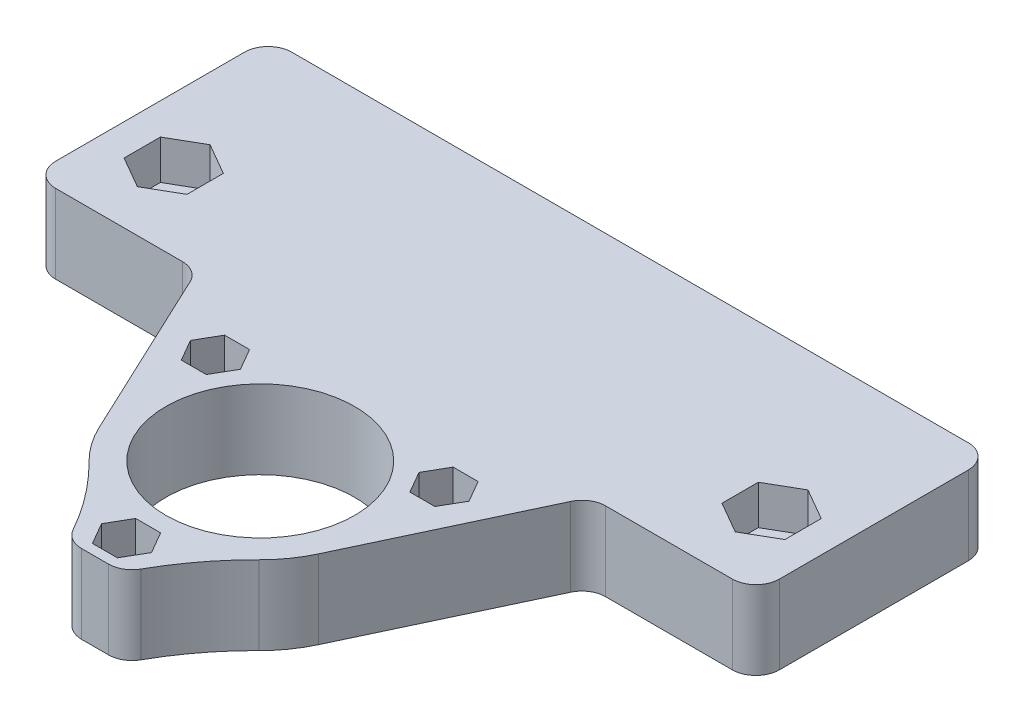
SolidWorks part; units mm, degrees
material "ABS"
ref_plane "Front" through (0, 0, 0) normal (0, 0, 1) x (1, 0, 0)
ref_plane "Top" through (0, 0, 0) normal (0, 1, 0) x (1, 0, 0)
ref_plane "Right" through (0, 0, 0) normal (1, 0, 0) x (0, 0, -1)
sketch "Esquisse1" plane through (0, 0, 0) normal (0, 1, 0) x (1, 0, 0)
  line L0 (0, -50) -> (0, 50) construction
  circle A0 centre (0, -77) radius 12
  circle A1 centre (-38, -50) radius 2.5
  circle A3 centre (-37.5, -115) radius 38
  circle A4 centre (37.5, -115) radius 38
  circle A5 centre (38, -50) radius 2.5
  dimension "D1" = 115
  dimension "D2" = 75
  dimension "D3" = 76
  dimension "D4" = 76
  dimension "D5" = 50
  dimension "D6" = 5
  dimension "D7" = 24
  dimension "D8" = 77
sketch "Esquisse2" plane through (0, 0, 0) normal (0, 1, 0) x (1, 0, 0)
  line L0 (0, -98) -> (-3.5147, -98)
  line L1 (-46, -30) -> (0, -30)
  line L2 (-46, -30) -> (-46, -60)
  line L4 (0, -30) -> (0, -43.5)
  line L5 (0, -89) -> (0, -98)
  line L6 (-46, -60) -> (-25, -60)
  line L7 (-25, -60) -> (-13.9246, -83.5489)
  line L8 (0, -46.5) -> (0, -65)
  line L9 (0, -43.5) -> (0, -46.5)
  circle A0 centre (-38, -50) radius 2.5 construction
  circle A1 centre (0, -77) radius 12 construction
  circle A2 centre (-37.5, -115) radius 38 construction
  circle A3 centre (-38, -50) radius 2.5
  arc A4 (0, -65) -> (0, -89) centre (0, -77) ccw
  arc A5 (-3.5147, -98) -> (-10.8085, -87.9526) centre (-37.5, -115) ccw
  arc A6 (-13.9246, -83.5489) -> (-10.8085, -87.9526) centre (0, -77) ccw
  arc A8 (0, -43.5) -> (0, -46.5) centre (0, -45) ccw construction
  dimension "D1" = 20
  dimension "D4" = 15.3877
  dimension "D5" = 10
  dimension "D7" = 3
  dimension "D8" = 45
  dimension "D2" = 8
  dimension "D3" = 98
  dimension "D6" = 25
extrude "Boss.-Extru.1" add sketch "Esquisse2" along normal blind 10
fillet "Congé1" radius 3 4 edges at (-46, 5, 30) (-46, 5, 60) (-25, 5, 60) (-3.5147, 5, 98)
sketch "Esquisse3" plane through (0, 0, 30) normal (0, 0, -1) x (-1, 0, 0)
  line L0 (0, 21) -> (20, 21) construction
  line L1 (0, 41) -> (20, 41)
  line L2 (0, 1) -> (20, 1)
  line L3 (0, 10) -> (0, 0) construction
  line L4 (0, 0) -> (43, 0) construction
  arc A0 (0, 41) -> (0, 1) centre (0, 21) ccw
  arc A1 (20, 1) -> (20, 41) centre (20, 21) ccw
  point P2 (10, 21)
  dimension "D1" = 21
  dimension "D2" = 40
  dimension "D3" = 20
extrude "Enlèv. mat.-Extru.1" [suppressed] cut sketch "Esquisse3" against normal blind 10
mirror "Symétrie1"
sketch "Esquisse4" plane through (0, 10, 0) normal (0, 1, 0) x (1, 0, 0)
  line L0 (-24.1895, -61.7232) -> (-13.9246, -83.5489) construction
  line L1 (0, -50) -> (0, 50) construction
  circle A0 centre (-14.527, -68.1701) radius 1.25
  circle A1 centre (0, -94) radius 1.25
  circle A2 centre (0, -77) radius 17 construction
  circle A3 centre (14.527, -68.1701) radius 1.25
  dimension "D1" = 6
  dimension "D2" = 34
  dimension "D3" = 2.5
extrude "Enlèv. mat.-Extru.2" cut sketch "Esquisse4" against normal through all
sketch "Esquisse5" plane through (0, 10, 0) normal (0, 1, 0) x (1, 0, 0)
  line L1 (-11.3516, -68.1701) -> (-12.9393, -65.4201)
  line L2 (-12.9393, -65.4201) -> (-16.1147, -65.4201)
  line L3 (-16.1147, -65.4201) -> (-17.7024, -68.1701)
  line L4 (-17.7024, -68.1701) -> (-16.1147, -70.9201)
  line L5 (-16.1147, -70.9201) -> (-12.9393, -70.9201)
  line L6 (-12.9393, -70.9201) -> (-11.3516, -68.1701)
  line L7 (17.7024, -68.1701) -> (16.1147, -65.4201)
  line L8 (16.1147, -65.4201) -> (12.9393, -65.4201)
  line L9 (12.9393, -65.4201) -> (11.3516, -68.1701)
  line L10 (11.3516, -68.1701) -> (12.9393, -70.9201)
  line L11 (12.9393, -70.9201) -> (16.1147, -70.9201)
  line L12 (16.1147, -70.9201) -> (17.7024, -68.1701)
  line L13 (3.1754, -94) -> (1.5877, -91.25)
  line L14 (1.5877, -91.25) -> (-1.5877, -91.25)
  line L15 (-1.5877, -91.25) -> (-3.1754, -94)
  line L16 (-3.1754, -94) -> (-1.5877, -96.75)
  line L17 (-1.5877, -96.75) -> (1.5877, -96.75)
  line L18 (1.5877, -96.75) -> (3.1754, -94)
  line L19 (-34, -47.6906) -> (-38, -45.3812)
  line L20 (-38, -45.3812) -> (-42, -47.6906)
  line L21 (-42, -47.6906) -> (-42, -52.3094)
  line L22 (-42, -52.3094) -> (-38, -54.6188)
  line L23 (-38, -54.6188) -> (-34, -52.3094)
  line L24 (-34, -52.3094) -> (-34, -47.6906)
  line L25 (42, -52.3094) -> (42, -47.6906)
  line L26 (42, -47.6906) -> (38, -45.3812)
  line L27 (38, -45.3812) -> (34, -47.6906)
  line L28 (34, -47.6906) -> (34, -52.3094)
  line L29 (34, -52.3094) -> (38, -54.6188)
  line L30 (38, -54.6188) -> (42, -52.3094)
  circle A0 centre (-14.527, -68.1701) radius 2.75 construction
  circle A1 centre (14.527, -68.1701) radius 2.75 construction
  circle A2 centre (0, -94) radius 2.75 construction
  circle A3 centre (-38, -50) radius 4 construction
  circle A4 centre (38, -50) radius 4 construction
  dimension "D1" = 5.5
  dimension "D2" = 8
extrude "Enlèv. mat.-Extru.3" cut sketch "Esquisse5" against normal blind 5
